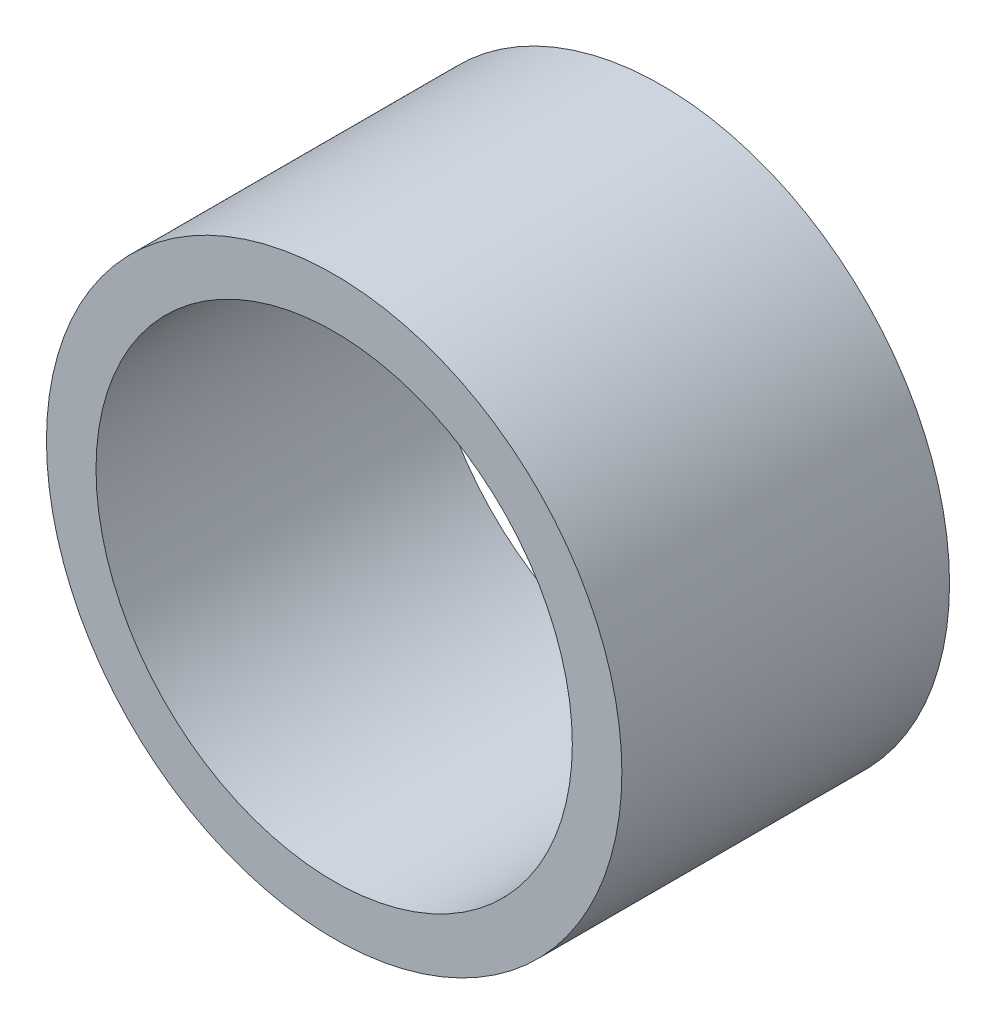
SolidWorks part; units mm, degrees
ref_plane "Front Plane" through (0, 0, 0) normal (0, 0, 1) x (1, 0, 0)
ref_plane "Top Plane" through (0, 0, 0) normal (0, 1, 0) x (1, 0, 0)
ref_plane "Right Plane" through (0, 0, 0) normal (1, 0, 0) x (0, 0, -1)
sketch "Sketch1" plane through (0, 0, 0) normal (0, 0, 1) x (1, 0, 0)
  circle A0 centre (0, 0) radius 29.8
  circle A1 centre (0, 0) radius 36
  dimension "D1" = 59.6
  dimension "D2" = 72
extrude "Boss-Extrude1" add sketch "Sketch1" along normal blind 41
